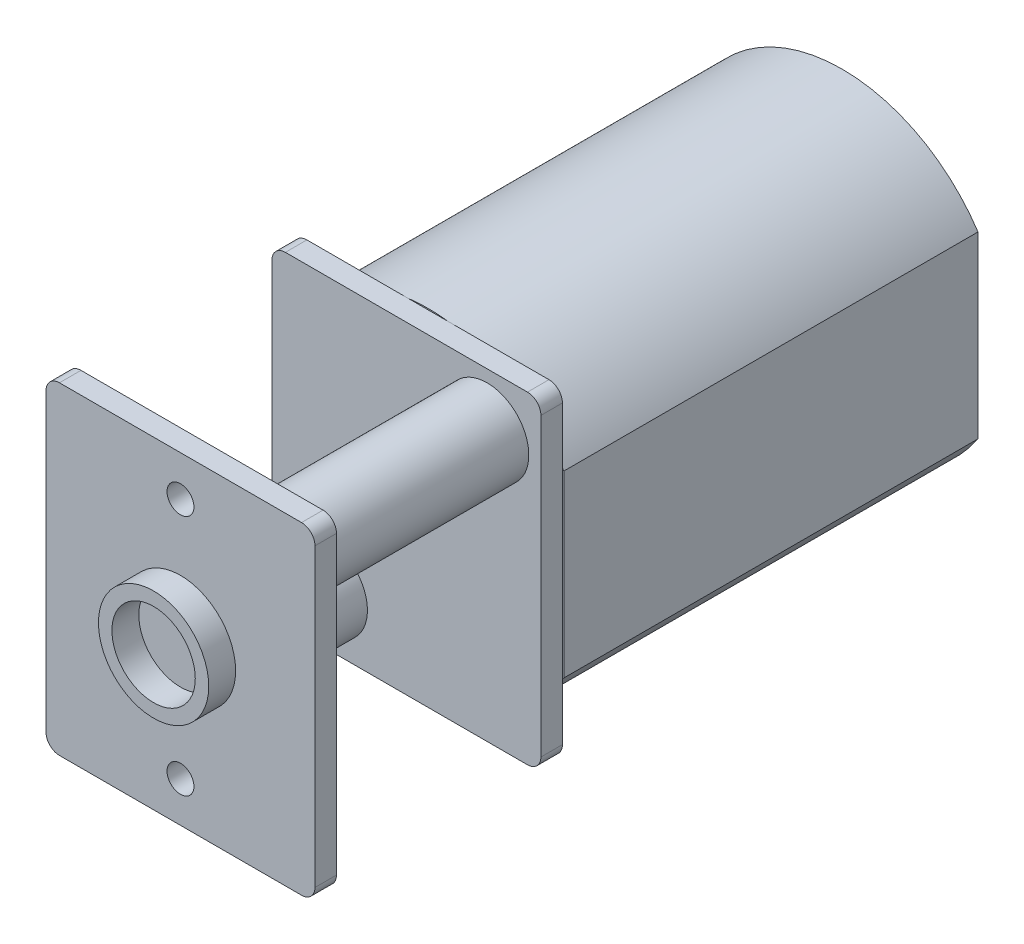
SolidWorks part; units mm, degrees
ref_plane "Спереди" through (0, 0, 0) normal (0, 0, 1) x (1, 0, 0)
ref_plane "Сверху" through (0, 0, 0) normal (0, 1, 0) x (1, 0, 0)
ref_plane "Справа" through (0, 0, 0) normal (1, 0, 0) x (0, 0, -1)
sketch "Эскиз1" plane through (0, 0, 0) normal (0, 0, 1) x (1, 0, 0)
  line L0 (5.05, -3.3317) -> (5.05, 3.3317)
  line L1 (-5.05, -3.3317) -> (-5.05, 3.3317)
  arc A0 (5.05, 3.3317) -> (-5.05, 3.3317) centre (0, 0) ccw
  arc A1 (-5.05, -3.3317) -> (5.05, -3.3317) centre (0, 0) ccw
  dimension "D1" = 10.1
  dimension "D2" = 5.05
extrude "Бобышка-Вытянуть1" add sketch "Эскиз1" along normal blind 15.4
sketch "Эскиз2" plane through (0, 0, 0) normal (0, 0, -1) x (-1, 0, 0)
  circle A0 centre (0, 0) radius 2.52
  circle A1 centre (0, 0) radius 0.8
extrude "Бобышка-Вытянуть2" add sketch "Эскиз2" along normal blind 1.1
sketch "Эскиз5" plane through (0, 0, 15.4) normal (0, 0, 1) x (1, 0, 0)
  line L1 (5, 6) -> (-5, 6)
  line L2 (5, 6) -> (5, -6)
  line L3 (5, -6) -> (-5, -6)
  line L4 (-5, 6) -> (-5, -6)
  line L5 (5, 6) -> (-5, -6) construction
  line L6 (5, -6) -> (-5, 6) construction
  point P0 (0, 0)
  dimension "D1" = 12
  dimension "D2" = 10
extrude "Бобышка-Вытянуть3" add sketch "Эскиз5" along normal blind 0.8
sketch "Эскиз7" plane through (0, 0, 16.2) normal (0, 0, 1) x (1, 0, 0)
  circle A0 centre (3, 4) radius 1.55
  circle A1 centre (-3, -4) radius 1.55
  dimension "D1" = 8
  dimension "D5" = 3.1
  dimension "D6" = 3.1
  dimension "D2" = 3
  dimension "D3" = 6
  dimension "D4" = 4
extrude "Бобышка-Вытянуть4" add sketch "Эскиз7" along normal blind 7.6
sketch "Эскиз8" plane through (0, 0, 23.8) normal (0, 0, 1) x (1, 0, 0)
  line L4 (-5, 6) -> (-5, -6)
  line L5 (-5, -6) -> (5, -6)
  line L6 (5, -6) -> (5, 6)
  line L7 (5, 6) -> (-5, 6)
  line L8 (-5, 6) -> (-5, -6)
  line L9 (-5, -6) -> (5, -6)
  line L10 (5, -6) -> (5, 6)
  line L11 (5, 6) -> (-5, 6)
  dimension "D1" = 0
extrude "Бобышка-Вытянуть5" add sketch "Эскиз8" along normal blind 0.8
sketch "Эскиз9" plane through (0, 0, 24.6) normal (0, 0, 1) x (1, 0, 0)
  circle A0 centre (0, 0) radius 2.05
  circle A1 centre (0, 0) radius 1.55
  dimension "D1" = 4.1
  dimension "D2" = 3.1
extrude "Бобышка-Вытянуть6" add sketch "Эскиз9" along normal blind 1
fillet "Скругление1" radius 0.5 8 edges at (-5, 6, 15.8) (5, 6, 15.8) (5, 6, 24.2) (-5, 6, 24.2) (-5, -6, 15.8) (-5, -6, 24.2) (5, -6, 15.8) (5, -6, 24.2)
sketch "Эскиз10" plane through (0, 0, 24.6) normal (0, 0, 1) x (1, 0, 0)
  circle A0 centre (0, -4.5) radius 0.5
  circle A1 centre (0, 4.5) radius 0.5
  point P4 (0, 0)
  dimension "D1" = 1
  dimension "D2" = 1
  dimension "D3" = 9
  dimension "D4" = 4.5
extrude "Вырез-Вытянуть1" cut sketch "Эскиз10" against normal up to next
